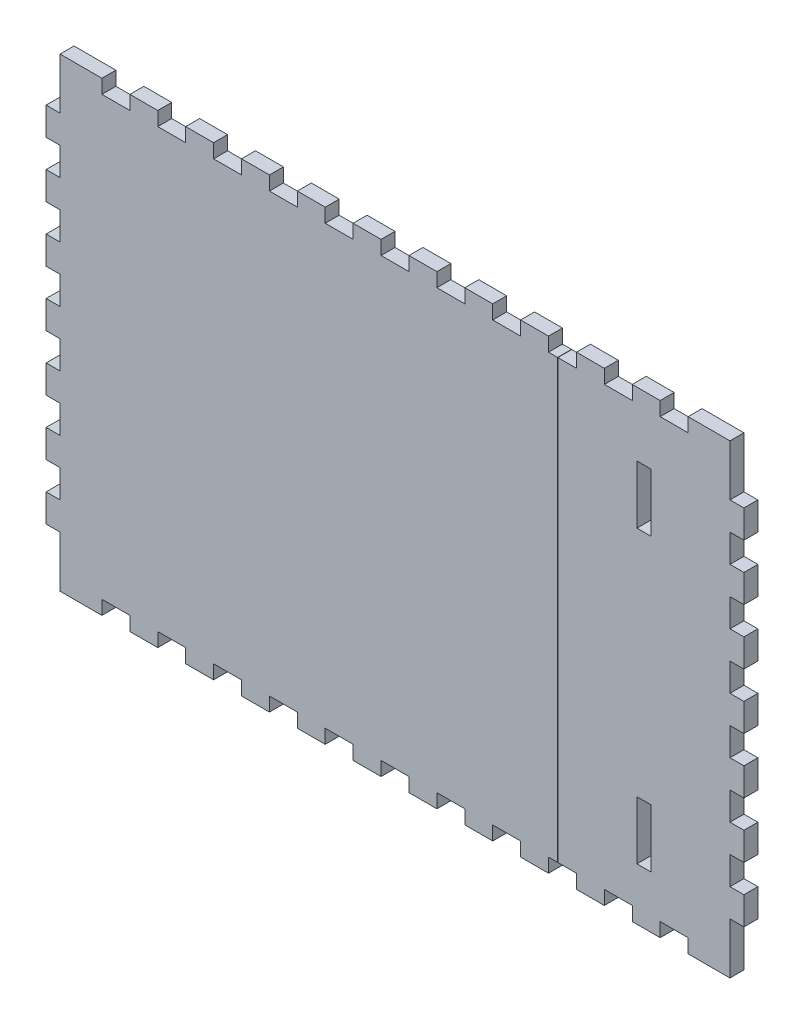
SolidWorks part; units mm, degrees
ref_plane "Front Plane" through (0, 0, 0) normal (0, 0, 1) x (1, 0, 0)
ref_plane "Top Plane" through (0, 0, 0) normal (0, 1, 0) x (1, 0, 0)
ref_plane "Right Plane" through (0, 0, 0) normal (1, 0, 0) x (0, 0, -1)
sketch "Model" plane through (0, 0, 0) normal (0, 0, 1) x (1, 0, 0)
  line L0 (209, 203) -> (209, 181)
  line L1 (209, 181) -> (203, 181)
  line L2 (203, 181) -> (203, 169)
  line L3 (203, 169) -> (209, 169)
  line L4 (209, 169) -> (209, 157)
  line L5 (209, 157) -> (203, 157)
  line L6 (203, 157) -> (203, 145)
  line L7 (203, 145) -> (209, 145)
  line L8 (209, 145) -> (209, 133)
  line L9 (209, 133) -> (203, 133)
  line L10 (203, 133) -> (203, 121)
  line L11 (203, 121) -> (209, 121)
  line L12 (209, 121) -> (209, 109)
  line L13 (209, 109) -> (203, 109)
  line L14 (203, 109) -> (203, 97)
  line L15 (203, 97) -> (209, 97)
  line L16 (209, 97) -> (209, 85)
  line L17 (209, 85) -> (203, 85)
  line L18 (203, 85) -> (203, 73)
  line L19 (203, 73) -> (209, 73)
  line L20 (209, 73) -> (209, 61)
  line L21 (209, 61) -> (203, 61)
  line L22 (203, 61) -> (203, 49)
  line L23 (203, 49) -> (209, 49)
  line L24 (209, 49) -> (209, 37)
  line L25 (209, 37) -> (203, 37)
  line L26 (203, 37) -> (203, 25)
  line L27 (203, 25) -> (209, 25)
  line L28 (209, 25) -> (209, 13)
  line L29 (209, 13) -> (209, 3)
  line L30 (209, 3) -> (227, 3)
  line L31 (227, 3) -> (227, 9)
  line L32 (227, 9) -> (239, 9)
  line L33 (239, 9) -> (239, 3)
  line L34 (239, 3) -> (251, 3)
  line L35 (251, 3) -> (251, 9)
  line L36 (251, 9) -> (263, 9)
  line L37 (263, 9) -> (263, 3)
  line L38 (263, 3) -> (275, 3)
  line L39 (275, 3) -> (275, 9)
  line L40 (275, 9) -> (287, 9)
  line L41 (287, 9) -> (287, 3)
  line L42 (287, 3) -> (299, 3)
  line L43 (299, 3) -> (299, 9)
  line L44 (299, 9) -> (311, 9)
  line L45 (311, 9) -> (311, 3)
  line L46 (311, 3) -> (323, 3)
  line L47 (323, 3) -> (323, 9)
  line L48 (323, 9) -> (335, 9)
  line L49 (335, 9) -> (335, 3)
  line L50 (335, 3) -> (347, 3)
  line L51 (347, 3) -> (347, 9)
  line L52 (347, 9) -> (359, 9)
  line L53 (359, 9) -> (359, 3)
  line L54 (359, 3) -> (371, 3)
  line L55 (371, 3) -> (371, 9)
  line L56 (371, 9) -> (383, 9)
  line L57 (383, 9) -> (383, 3)
  line L58 (383, 3) -> (395, 3)
  line L59 (395, 3) -> (395, 9)
  line L60 (395, 9) -> (407, 9)
  line L61 (407, 9) -> (407, 3)
  line L62 (407, 3) -> (419, 3)
  line L63 (419, 3) -> (419, 9)
  line L64 (419, 9) -> (431, 9)
  line L65 (431, 9) -> (431, 3)
  line L66 (431, 3) -> (443, 3)
  line L67 (443, 3) -> (443, 9)
  line L68 (443, 9) -> (455, 9)
  line L69 (455, 9) -> (455, 3)
  line L70 (455, 3) -> (467, 3)
  line L71 (467, 3) -> (467, 9)
  line L72 (467, 9) -> (479, 9)
  line L73 (479, 9) -> (479, 3)
  line L74 (479, 3) -> (491, 3)
  line L75 (491, 3) -> (497, 3)
  line L76 (497, 3) -> (497, 25)
  line L77 (497, 25) -> (503, 25)
  line L78 (503, 25) -> (503, 37)
  line L79 (503, 37) -> (497, 37)
  line L80 (497, 37) -> (497, 49)
  line L81 (497, 49) -> (503, 49)
  line L82 (503, 49) -> (503, 61)
  line L83 (503, 61) -> (497, 61)
  line L84 (497, 61) -> (497, 73)
  line L85 (497, 73) -> (503, 73)
  line L86 (503, 73) -> (503, 85)
  line L87 (503, 85) -> (497, 85)
  line L88 (497, 85) -> (497, 97)
  line L89 (497, 97) -> (503, 97)
  line L90 (503, 97) -> (503, 109)
  line L91 (503, 109) -> (497, 109)
  line L92 (497, 109) -> (497, 121)
  line L93 (497, 121) -> (503, 121)
  line L94 (503, 121) -> (503, 133)
  line L95 (503, 133) -> (497, 133)
  line L96 (497, 133) -> (497, 145)
  line L97 (497, 145) -> (503, 145)
  line L98 (503, 145) -> (503, 157)
  line L99 (503, 157) -> (497, 157)
  line L100 (497, 157) -> (497, 169)
  line L101 (497, 169) -> (503, 169)
  line L102 (503, 169) -> (503, 181)
  line L103 (503, 181) -> (497, 181)
  line L104 (497, 181) -> (497, 193)
  line L105 (497, 193) -> (497, 203)
  line L106 (497, 203) -> (479, 203)
  line L107 (479, 203) -> (479, 197)
  line L108 (479, 197) -> (467, 197)
  line L109 (467, 197) -> (467, 203)
  line L110 (467, 203) -> (455, 203)
  line L111 (455, 203) -> (455, 197)
  line L112 (455, 197) -> (443, 197)
  line L113 (443, 197) -> (443, 203)
  line L114 (443, 203) -> (431, 203)
  line L115 (431, 203) -> (431, 197)
  line L116 (431, 197) -> (419, 197)
  line L117 (419, 197) -> (419, 203)
  line L118 (419, 203) -> (407, 203)
  line L119 (407, 203) -> (407, 197)
  line L120 (407, 197) -> (395, 197)
  line L121 (395, 197) -> (395, 203)
  line L122 (395, 203) -> (383, 203)
  line L123 (383, 203) -> (383, 197)
  line L124 (383, 197) -> (371, 197)
  line L125 (371, 197) -> (371, 203)
  line L126 (371, 203) -> (359, 203)
  line L127 (359, 203) -> (359, 197)
  line L128 (359, 197) -> (347, 197)
  line L129 (347, 197) -> (347, 203)
  line L130 (347, 203) -> (335, 203)
  line L131 (335, 203) -> (335, 197)
  line L132 (335, 197) -> (323, 197)
  line L133 (323, 197) -> (323, 203)
  line L134 (323, 203) -> (311, 203)
  line L135 (311, 203) -> (311, 197)
  line L136 (311, 197) -> (299, 197)
  line L137 (299, 197) -> (299, 203)
  line L138 (299, 203) -> (287, 203)
  line L139 (287, 203) -> (287, 197)
  line L140 (287, 197) -> (275, 197)
  line L141 (275, 197) -> (275, 203)
  line L142 (275, 203) -> (263, 203)
  line L143 (263, 203) -> (263, 197)
  line L144 (263, 197) -> (251, 197)
  line L145 (251, 197) -> (251, 203)
  line L146 (251, 203) -> (239, 203)
  line L147 (239, 203) -> (239, 197)
  line L148 (239, 197) -> (227, 197)
  line L149 (227, 197) -> (227, 203)
  line L150 (227, 203) -> (215, 203)
  line L151 (215, 203) -> (209, 203)
extrude "Boss-Extrude1" add sketch "Model" along normal blind 6
sketch "Sketch2" plane through (0, 0, 6) normal (0, 0, 1) x (1, 0, 0)
  line L0 (497, 181) -> (497, 203) construction
  line L1 (422.9, 218.155) -> (423, 218.155)
  line L2 (422.9, 218.155) -> (422.9, -17.155)
  line L3 (422.9, -17.155) -> (423, -17.155)
  line L4 (423, 218.155) -> (423, -17.155)
  line L5 (423, 100.5) -> (503, 100.5)
  line L6 (503, 97) -> (503, 109) construction
  line L7 (457, 163) -> (423, 163)
  line L9 (463, 163) -> (497, 163)
  line L11 (497, 157) -> (497, 169) construction
  line L12 (457, 175.5) -> (463, 175.5)
  line L13 (457, 175.5) -> (457, 150.5)
  line L14 (457, 150.5) -> (463, 150.5)
  line L15 (463, 175.5) -> (463, 150.5)
  line L16 (457, 50.5) -> (463, 50.5)
  line L19 (463, 25.5) -> (463, 50.5)
  line L20 (457, 25.5) -> (463, 25.5)
  line L21 (457, 25.5) -> (457, 50.5)
  dimension "D1" = 0.1
  dimension "D2" = 74
  dimension "D3" = 6
  dimension "D4" = 25
  dimension "D5" = 50
extrude "Cut-Extrude1" cut sketch "Sketch2" against normal blind 6 contours L21 L20 L19 L16 | L4 L1 L2 L3 | L13 L14 L15 L12
